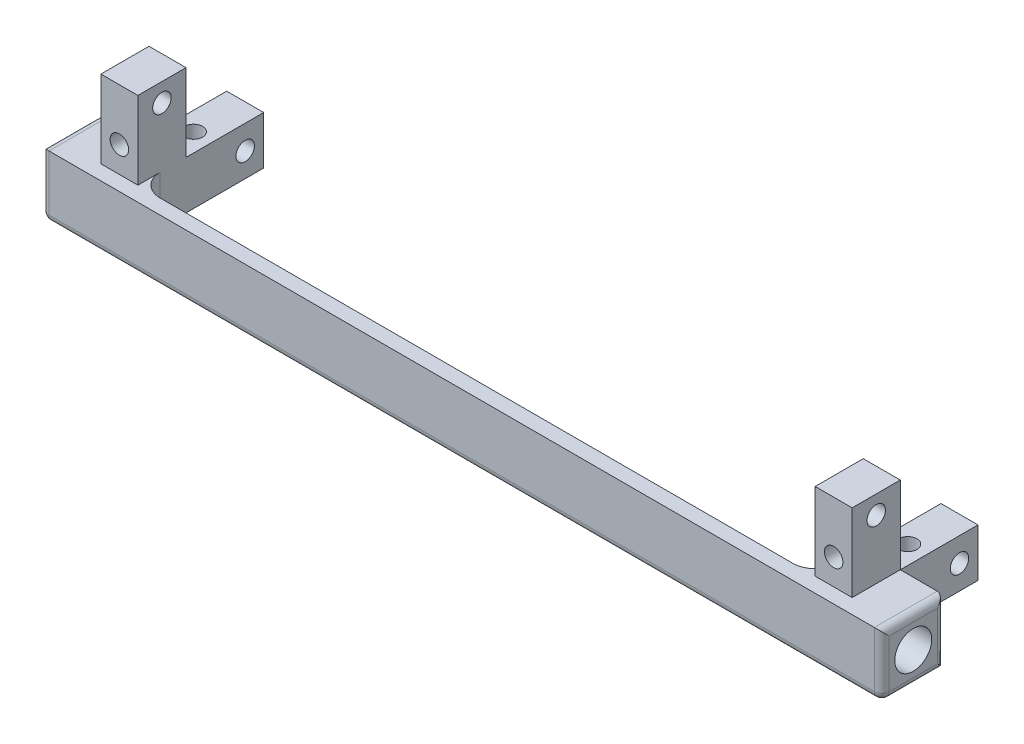
SolidWorks part; units mm, degrees
ref_plane "Front Plane" through (0, 0, 0) normal (0, 0, 1) x (1, 0, 0)
ref_plane "Top Plane" through (0, 0, 0) normal (0, 1, 0) x (1, 0, 0)
ref_plane "Right Plane" through (0, 0, 0) normal (1, 0, 0) x (0, 0, -1)
sketch "Sketch1" plane through (0, 0, 0) normal (0, 0, 1) x (1, 0, 0)
  line L1 (56.75, -4.25) -> (-56.75, -4.25)
  line L2 (56.75, -4.25) -> (56.75, 4.25)
  line L3 (56.75, 4.25) -> (-56.75, 4.25)
  line L4 (-56.75, -4.25) -> (-56.75, 4.25)
  line L5 (56.75, -4.25) -> (-56.75, 4.25) construction
  line L6 (56.75, 4.25) -> (-56.75, -4.25) construction
  point P0 (0, 0)
  dimension "D1" = 113.5
  dimension "D2" = 8.5
extrude "Boss-Extrude1" add sketch "Sketch1" along normal blind 8.5
ref_plane "Plane4" through (50.75, 0, 0) normal (1, 0, 0) x (0, 0, -1)
sketch "Sketch4" plane through (50.75, 0, 0) normal (1, 0, 0) x (0, 0, -1)
  line L0 (0, -2.25) -> (10.5, -2.25)
  line L1 (0, -4.25) -> (0, 4.25) construction
  line L2 (10.5, -2.25) -> (10.5, 14.75)
  line L3 (10.5, 14.75) -> (-6.5, 14.75)
  line L4 (-6.5, 14.75) -> (-6.5, 4.25)
  line L5 (-8.5, 4.25) -> (0, 4.25) construction
  line L6 (-8.5, -4.25) -> (0, -4.25) construction
  line L7 (-8.5, -4.25) -> (-8.5, 4.25) construction
  line L12 (0, -4.25) -> (0, 4.25)
  line L13 (0, 4.25) -> (-8.5, 4.25)
  line L14 (-8.5, 4.25) -> (-8.5, -4.25)
  line L15 (-8.5, -4.25) -> (0, -4.25)
  line L16 (0, -2.25) -> (0, 4.25)
  line L17 (0, 4.25) -> (-6.5, 4.25)
  dimension "D1" = 2
  dimension "D2" = 2
  dimension "D3" = 10.5
  dimension "D4" = 10.5
  dimension "D5" = 0
extrude "Boss-Extrude2" add sketch "Sketch4" against normal blind 5
ref_plane "Plane7" through (-50.75, 0, 0) normal (-1, 0, 0) x (0, 0, 1)
sketch "Sketch12" plane through (-50.75, 0, 0) normal (-1, 0, 0) x (0, 0, 1)
  line L0 (6.5, 4.25) -> (6.5, 14.75)
  line L1 (6.5, 14.75) -> (-10.5, 14.75)
  line L2 (-10.5, 14.75) -> (-10.5, -2.25)
  line L3 (-10.5, -2.25) -> (0, -2.25)
  line L4 (0, -2.25) -> (0, 4.25)
  line L5 (0, 4.25) -> (6.5, 4.25)
extrude "Boss-Extrude3" add sketch "Sketch12" against normal blind 5
sketch "Sketch13" plane through (0, 4.25, 0) normal (0, 1, 0) x (1, 0, 0)
  line L1 (-45.75, 0) -> (45.75, 0)
  line L2 (-45.75, 0) -> (-45.75, -6.5)
  line L3 (-45.75, -6.5) -> (45.75, -6.5)
  line L4 (45.75, 0) -> (45.75, -6.5)
extrude "Cut-Extrude1" cut sketch "Sketch13" against normal blind 6.5
hole_wizard "M3x0.5 Tapped Hole1" positions "Sketch16" profile "Sketch15" tap size "M3x0.5" standard "Ansi Metric"
sketch "Sketch16" plane through (0, 0, 6.5) normal (0, 0, 1) x (1, 0, 0)
  line L0 (-45.75, 4.25) -> (-50.75, 4.25) construction
  line L3 (-45.75, 4.25) -> (-45.75, 14.75) construction
  point P0 (-48.25, 7.75)
  dimension "D1" = 3.5
  dimension "D2" = 2.5
sketch "Sketch15" plane through (-48.25, 7.75, 6.5) normal (1, 0, 0) x (0, -1, 0)
  line L0 (0, 0) -> (0, 8.2511)
  line L1 (0, 8.2511) -> (1.25, 7.5)
  line L2 (1.25, 7.5) -> (1.25, 0)
  line L5 (1.25, 0) -> (0, 0)
  line L10 (0, 8.2511) -> (-1.25, 7.5) construction
  line L11 (0, -6.35) -> (0, 107.95) construction
  dimension "Tap Drill Dia." = 2.5
  dimension "Tap Drill Depth" = 7.5
  dimension "Drill Angle" = 118
cosmetic thread "Hole Thread1" parameters "D1"=6, "D2"=3
hole_wizard "M3x0.5 Tapped Hole2" positions "Sketch18" profile "Sketch19" tap size "M3x0.5" standard "Ansi Metric"
sketch "Sketch18" plane through (-50.75, 0, 0) normal (-1, 0, 0) x (0, 0, 1)
  line L0 (6.5, 4.25) -> (6.5, 14.75) construction
  line L1 (8.5, 4.25) -> (0, 4.25) construction
  point P0 (3.25, 12.25)
  dimension "D1" = 3.25
  dimension "D2" = 8
sketch "Sketch19" plane through (-50.75, 12.25, 3.25) normal (0, 1, 0) x (0, 0, 1)
  line L0 (0, 0) -> (0, 5)
  line L1 (0, 5) -> (1.25, 5)
  line L2 (1.25, 5) -> (1.25, 0)
  line L5 (1.25, 0) -> (0, 0)
  line L11 (0, -6.35) -> (0, 107.95) construction
  dimension "Thru Tap Drill Dia." = 2.5
  dimension "Thru Tap Drill Depth" = 5
cosmetic thread "Hole Thread9" parameters "D2"=3
hole_wizard "M3x0.5 Tapped Hole3" positions "Sketch21" profile "Sketch20" tap size "M3x0.5" standard "Ansi Metric"
sketch "Sketch21" plane through (-50.75, 0, 0) normal (-1, 0, 0) x (0, 0, 1)
  line L0 (0, 4.25) -> (0, -4.25) construction
  line L1 (-10.5, -2.25) -> (0, -2.25) construction
  point P0 (-8, 1)
  dimension "D1" = 8
  dimension "D2" = 3.25
cosmetic thread "Hole Thread3" parameters "D2"=3
sketch "Sketch20" plane through (-50.75, 1, -8) normal (0, 1, 0) x (0, 0, 1)
  line L0 (0, 0) -> (0, 5)
  line L1 (0, 5) -> (1.25, 5)
  line L2 (1.25, 5) -> (1.25, 0)
  line L5 (1.25, 0) -> (0, 0)
  line L11 (0, -6.35) -> (0, 107.95) construction
  dimension "Thru Tap Drill Dia." = 2.5
  dimension "Thru Tap Drill Depth" = 5
hole_wizard "M3x0.5 Tapped Hole4" positions "Sketch23" profile "Sketch22" tap size "M3x0.5" standard "Ansi Metric"
sketch "Sketch23" plane through (0, -2.25, 0) normal (0, -1, 0) x (1, 0, 0)
  line L1 (-45.75, -10.5) -> (-45.75, 0) construction
  line L2 (-56.75, 0) -> (56.75, 0) construction
  point P0 (-48.25, -3.5)
  dimension "D1" = 2.5
  dimension "D2" = 3.5
sketch "Sketch22" plane through (-48.25, -2.25, -3.5) normal (1, 0, 0) x (0, 0, -1)
  line L0 (0, 0) -> (0, 8.2511)
  line L1 (0, 8.2511) -> (1.25, 7.5)
  line L2 (1.25, 7.5) -> (1.25, 0)
  line L5 (1.25, 0) -> (0, 0)
  line L10 (0, 8.2511) -> (-1.25, 7.5) construction
  line L11 (0, -6.35) -> (0, 107.95) construction
  dimension "Tap Drill Dia." = 2.5
  dimension "Tap Drill Depth" = 7.5
  dimension "Drill Angle" = 118
cosmetic thread "Hole Thread5" parameters "D1"=6, "D2"=3
fillet "Fillet1" radius 1 1 edges at (0, -4.25, 8.5)
fillet "Fillet2" radius 1 5 edges at (-56.75, -4.25, 3.75) (-56.75, -3.9571, 8.2071) (-56.75, 4.25, 4.25) (-56.75, 0, 0) (-56.75, 0.5, 8.5)
fillet "Fillet3" radius 1 5 edges at (56.75, -4.25, 3.75) (56.75, -3.9571, 8.2071) (56.75, 0, 0) (56.75, 0.5, 8.5) (56.75, 4.25, 4.25)
fillet "Fillet4" radius 3 2 edges at (45.75, 1, 6.5) (-45.75, 1, 6.5)
hole_wizard "M3x0.5 Tapped Hole5" positions "Sketch28" profile "Sketch27" tap size "M3x0.5" standard "Ansi Metric"
sketch "Sketch28" plane through (0, 0, 6.5) normal (0, 0, 1) x (1, 0, 0)
  line L0 (45.75, 14.75) -> (45.75, 4.25) construction
  line L3 (45.75, 4.25) -> (50.75, 4.25) construction
  point P0 (48.25, 7.75)
  dimension "D1" = 2.5
  dimension "D2" = 3.5
sketch "Sketch27" plane through (48.25, 7.75, 6.5) normal (1, 0, 0) x (0, -1, 0)
  line L0 (0, 0) -> (0, 8.2511)
  line L1 (0, 8.2511) -> (1.25, 7.5)
  line L2 (1.25, 7.5) -> (1.25, 0)
  line L5 (1.25, 0) -> (0, 0)
  line L10 (0, 8.2511) -> (-1.25, 7.5) construction
  line L11 (0, -6.35) -> (0, 107.95) construction
  dimension "Tap Drill Dia." = 2.5
  dimension "Tap Drill Depth" = 7.5
  dimension "Drill Angle" = 118
cosmetic thread "Hole Thread6" parameters "D1"=6, "D2"=3
hole_wizard "M3x0.5 Tapped Hole6" positions "Sketch30" profile "Sketch29" tap size "M3x0.5" standard "Ansi Metric"
sketch "Sketch30" plane through (0, -2.25, 0) normal (0, -1, 0) x (1, 0, 0)
  line L0 (45.75, 0) -> (50.75, 0) construction
  line L1 (45.75, 0) -> (45.75, -10.5) construction
  point P0 (48.25, -3.5)
  dimension "D1" = 3.5
  dimension "D2" = 2.5
sketch "Sketch29" plane through (48.25, -2.25, -3.5) normal (1, 0, 0) x (0, 0, -1)
  line L0 (0, 0) -> (0, 8.2511)
  line L1 (0, 8.2511) -> (1.25, 7.5)
  line L2 (1.25, 7.5) -> (1.25, 0)
  line L5 (1.25, 0) -> (0, 0)
  line L10 (0, 8.2511) -> (-1.25, 7.5) construction
  line L11 (0, -6.35) -> (0, 107.95) construction
  dimension "Tap Drill Dia." = 2.5
  dimension "Tap Drill Depth" = 7.5
  dimension "Drill Angle" = 118
cosmetic thread "Hole Thread7" parameters "D1"=6, "D2"=3
hole_wizard "M3x0.5 Tapped Hole7" positions "Sketch32" profile "Sketch31" tap size "M3x0.5" standard "Ansi Metric"
sketch "Sketch32" plane through (50.75, 0, 0) normal (1, 0, 0) x (0, 0, -1)
  line L0 (0, 4.25) -> (0, -2.25) construction
  line L1 (0, -2.25) -> (10.5, -2.25) construction
  point P0 (8, 1)
  dimension "D1" = 8
  dimension "D2" = 3.25
sketch "Sketch31" plane through (50.75, 1, -8) normal (0, 1, 0) x (0, 0, -1)
  line L0 (0, 0) -> (0, 8.2511)
  line L1 (0, 8.2511) -> (1.25, 7.5)
  line L2 (1.25, 7.5) -> (1.25, 0)
  line L5 (1.25, 0) -> (0, 0)
  line L10 (0, 8.2511) -> (-1.25, 7.5) construction
  line L11 (0, -6.35) -> (0, 107.95) construction
  dimension "Tap Drill Dia." = 2.5
  dimension "Tap Drill Depth" = 7.5
  dimension "Drill Angle" = 118
cosmetic thread "Hole Thread8" parameters "D1"=5, "D2"=3
hole_wizard "M3x0.5 Tapped Hole9" positions "Sketch36" profile "Sketch35" tap size "M3x0.5" standard "Ansi Metric"
sketch "Sketch36" plane through (50.75, 0, 0) normal (1, 0, 0) x (0, 0, -1)
  line L0 (-6.5, 4.25) -> (0, 4.25) construction
  line L1 (-6.5, 14.75) -> (-6.5, 4.25) construction
  point P0 (-3.25, 12.25)
  dimension "D1" = 8
  dimension "D2" = 3.25
sketch "Sketch35" plane through (50.75, 12.25, 3.25) normal (0, 1, 0) x (0, 0, -1)
  line L0 (0, 0) -> (0, 8.2511)
  line L1 (0, 8.2511) -> (1.25, 7.5)
  line L2 (1.25, 7.5) -> (1.25, 0)
  line L5 (1.25, 0) -> (0, 0)
  line L10 (0, 8.2511) -> (-1.25, 7.5) construction
  line L11 (0, -6.35) -> (0, 107.95) construction
  dimension "Tap Drill Dia." = 2.5
  dimension "Tap Drill Depth" = 7.5
  dimension "Drill Angle" = 118
cosmetic thread "Hole Thread11" parameters "D1"=5, "D2"=3
sketch "Sketch43" plane through (-50.75, 0, 0) normal (-1, 0, 0) x (0, 0, 1)
  line L1 (6.5, 14.75) -> (-10.5, 14.75) construction
  line L2 (-10.5, 14.75) -> (-10.5, -2.25) construction
  line L3 (-10.5, 4.25) -> (-10.5, 14.75)
  line L4 (-10.5, 14.75) -> (0, 14.75)
  line L5 (-10.5, 4.25) -> (0, 4.25)
  line L6 (0, 4.25) -> (0, 14.75)
  point P6 (-5.25, 4.25)
  point P9 (-5.25, 9.5)
  point P10 (0, 9.5)
extrude "Cut-Extrude3" cut sketch "Sketch43" against normal through all
sketch "Sketch44" plane through (56.75, 0, 0) normal (1, 0, 0) x (0, 0, -1)
  line L0 (-8.5, -3.25) -> (-8.5, 4.25) construction
  line L1 (-8.5, 4.25) -> (0, 4.25) construction
  circle A0 centre (-4.25, 0) radius 2.5
  dimension "D1" = 5
  dimension "D2" = 4.25
  dimension "D3" = 4.25
extrude "Cut-Extrude4" cut sketch "Sketch44" against normal blind 10
sketch "Sketch45" plane through (46.75, 0, 0) normal (1, 0, 0) x (0, 0, -1)
  circle A0 centre (-4.25, 0) radius 1.25
  dimension "D1" = 2.5
extrude "Cut-Extrude5" cut sketch "Sketch45" against normal up to next
hole_wizard "M6x1.0 Tapped Hole0" positions "Sketch49" profile "Sketch48" tap size "M6x1.0" standard "Ansi Metric"
sketch "Sketch49" plane through (56.75, 0, 0) normal (1, 0, 0) x (0, 0, -1)
  line L0 (-8.5, 4.25) -> (0, 4.25) construction
  line L1 (-8.5, -3.25) -> (-8.5, 4.25) construction
  point P0 (-4.25, 0)
  dimension "D1" = 4.25
  dimension "D2" = 4.25
sketch "Sketch48" plane through (56.75, 0, 4.25) normal (0, 1, 0) x (0, 0, -1)
  line L0 (0, 0) -> (0, 4.5122)
  line L1 (0, 4.5122) -> (2.5, 3.01)
  line L2 (2.5, 3.01) -> (2.5, 0)
  line L5 (2.5, 0) -> (0, 0)
  line L10 (0, 4.5122) -> (-2.5, 3.01) construction
  line L11 (0, -6.35) -> (0, 107.95) construction
  dimension "Tap Drill Dia." = 5
  dimension "Tap Drill Depth" = 3.01
  dimension "Drill Angle" = 118
